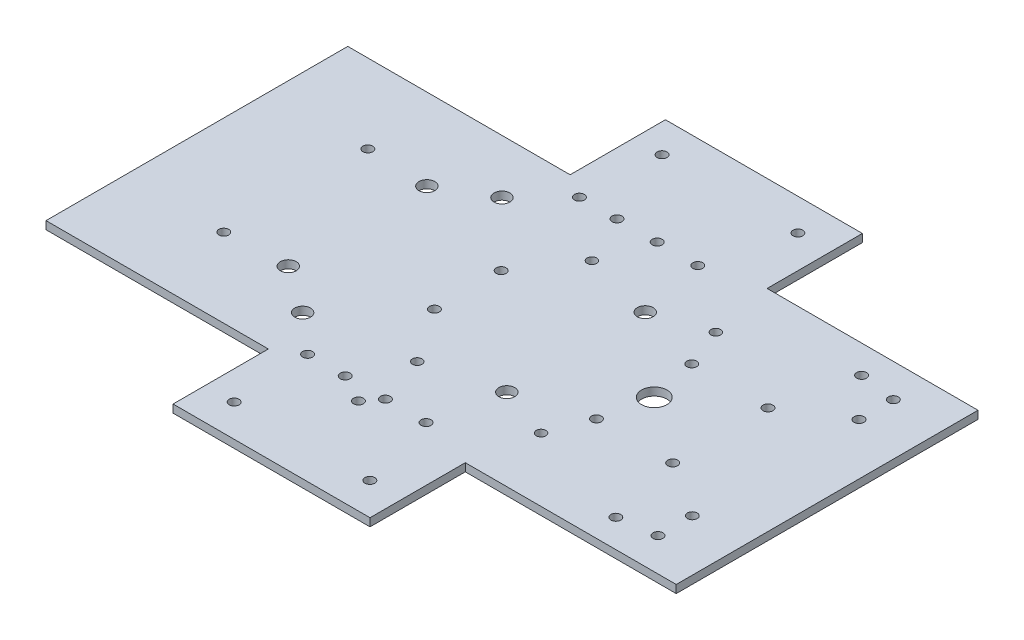
SolidWorks part; units mm, degrees
ref_plane "前视基准面" through (0, 0, 0) normal (0, 0, 1) x (1, 0, 0)
ref_plane "上视基准面" through (0, 0, 0) normal (0, 1, 0) x (1, 0, 0)
ref_plane "右视基准面" through (0, 0, 0) normal (1, 0, 0) x (0, 0, -1)
sketch "草图1" plane through (0, 0, 0) normal (0, 1, 0) x (1, 0, 0)
  line L1 (0, 95) -> (70, 95)
  line L2 (70, 95) -> (70, 125)
  line L3 (70, 125) -> (132, 125)
  line L4 (132, 125) -> (132, 95)
  line L8 (132, 0) -> (132, -30)
  line L9 (132, -30) -> (70, -30)
  line L10 (70, -30) -> (70, 0)
  line L12 (0, 47.5) -> (198.3957, 47.5) construction
  line L24 (122.7822, 47.5) -> (122.7822, 47.5586)
  line L28 (122.7822, 47.5586) -> (122.7822, 47.5)
  line L29 (198.3957, 95) -> (198.3957, 0)
  line L40 (0, 95) -> (0, 0)
  line L43 (132, 0) -> (198.3957, 0)
  line L44 (132, 95) -> (198.3957, 95)
  line L45 (0, 0) -> (70, 0)
  circle A0 centre (96.8555, 20) radius 1.5
  circle A1 centre (135.8555, 20) radius 1.5
  circle A2 centre (96.8555, 75) radius 1.5
  circle A3 centre (135.8555, 75) radius 1.5
  circle A4 centre (143.9183, 47.5687) radius 4
  circle A5 centre (65.4779, 15.3094) radius 2.5
  circle A6 centre (65.4779, 78.0609) radius 2.5
  circle A8 centre (50.5495, 69.3486) radius 2.5
  circle A9 centre (119.282, 69.3486) radius 2.5
  circle A10 centre (85.2822, 58) radius 1.55
  circle A11 centre (85.2822, 37) radius 1.55
  circle A12 centre (119.3028, 25.7652) radius 2.5
  circle A13 centre (50.5703, 25.6996) radius 2.5
  circle A14 centre (140.7051, 62.5729) radius 1.55
  circle A15 centre (164.7051, 62.5729) radius 1.55
  circle A16 centre (140.7051, 32.5729) radius 1.55
  circle A17 centre (164.7051, 32.5729) radius 1.55
  circle A18 centre (79.0742, -19.8484) radius 1.55
  circle A19 centre (121.8034, -19.8484) radius 1.55
  circle A20 centre (79.0099, 114.9238) radius 1.55
  circle A21 centre (121.7391, 114.9646) radius 1.55
  circle A22 centre (31.1378, 24.8257) radius 1.55
  circle A23 centre (31.1162, 70.204) radius 1.55
  circle A24 centre (77.5837, 90.3472) radius 1.55
  circle A25 centre (89.4069, 90.3472) radius 1.55
  circle A26 centre (98.3553, 0) radius 1.55
  circle A27 centre (102.0544, 90.3472) radius 1.55
  circle A31 centre (114.8409, 90.3472) radius 1.55
  circle A34 centre (114.8817, 4.7625) radius 1.55
  circle A35 centre (102.0953, 4.7503) radius 1.55
  circle A36 centre (89.4477, 4.7382) radius 1.55
  circle A37 centre (77.6246, 4.7269) radius 1.55
  circle A38 centre (170.5692, 86.1874) radius 1.55
  circle A39 centre (182.1949, 84.5461) radius 1.55
  circle A40 centre (182.1949, 73.7411) radius 1.55
  circle A41 centre (182.1949, 21.2589) radius 1.55
  circle A42 centre (182.1949, 10.4539) radius 1.55
  circle A43 centre (170.5692, 8.8126) radius 1.55
  dimension "D1" = 30
  dimension "D3" = 70
  dimension "D6" = 62
  dimension "D8" = 30
extrude "凸台-拉伸1" add sketch "草图1" along normal blind 2.5
